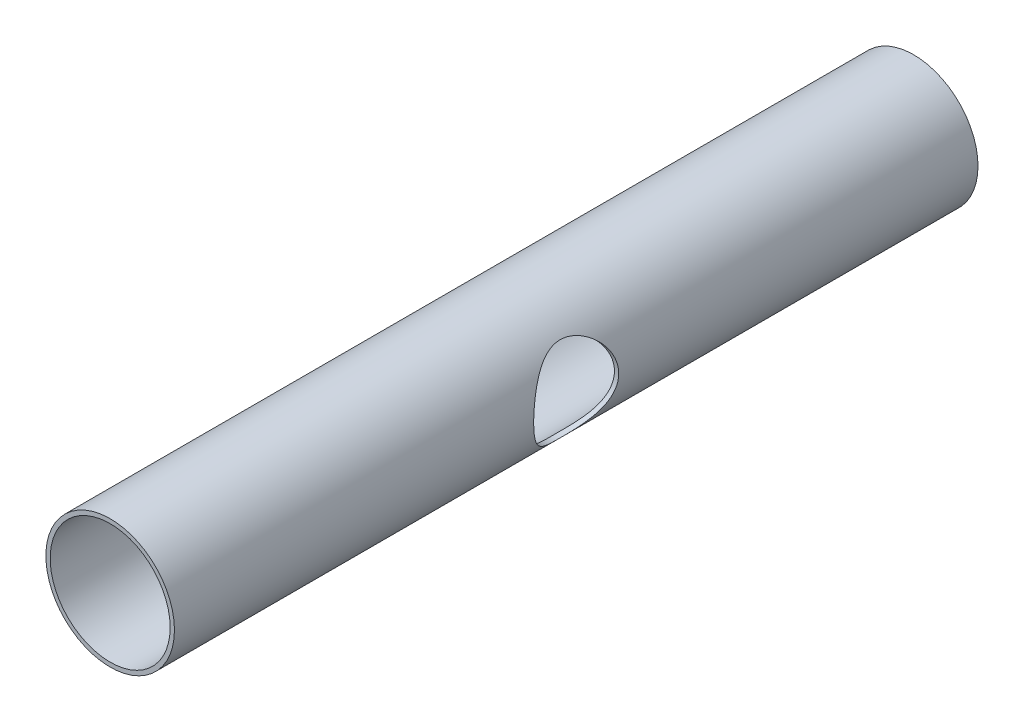
SolidWorks part; units mm, degrees
material "6061-T6 (SS)"
ref_plane "Front" through (0, 0, 0) normal (0, 0, 1) x (1, 0, 0)
ref_plane "Top" through (0, 0, 0) normal (0, 1, 0) x (1, 0, 0)
ref_plane "Right" through (0, 0, 0) normal (1, 0, 0) x (0, 0, -1)
sketch "Sketch1" plane through (0, 0, 0) normal (0, 0, 1) x (1, 0, 0)
  circle A0 centre (0, 0) radius 11.2
  circle A1 centre (0, 0) radius 12
  dimension "D1" = 24
  dimension "D2" = 0.8
extrude "Boss-Extrude1" add sketch "Sketch1" along normal mid plane 150
sketch "Sketch2" plane through (0, 0, 0) normal (1, 0, 0) x (0, 0, -1)
  circle A0 centre (0, 0) radius 7.9375
  dimension "D1" = 15.875
extrude "Cut-Extrude1" cut sketch "Sketch2" against normal through all both and the other way through all
